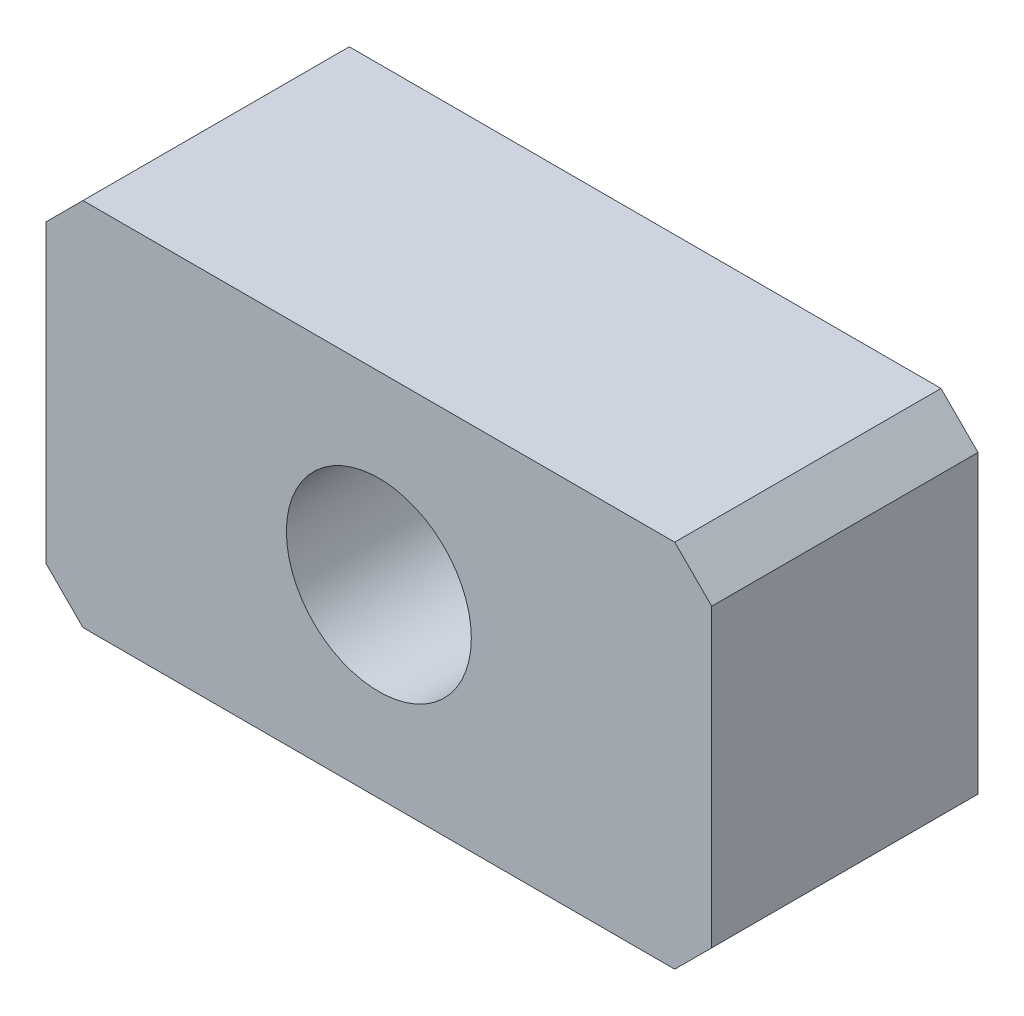
SolidWorks part; units mm, degrees
ref_plane "Front Plane" through (0, 0, 0) normal (0, 0, 1) x (1, 0, 0)
ref_plane "Top Plane" through (0, 0, 0) normal (0, 1, 0) x (1, 0, 0)
ref_plane "Right Plane" through (0, 0, 0) normal (1, 0, 0) x (0, 0, -1)
sketch "Sketch1" plane through (0, 0, 0) normal (0, 0, 1) x (1, 0, 0)
  line L1 (9, -5) -> (-9, -5)
  line L2 (9, -5) -> (9, 5)
  line L3 (9, 5) -> (-9, 5)
  line L4 (-9, -5) -> (-9, 5)
  line L5 (9, -5) -> (-9, 5) construction
  line L6 (9, 5) -> (-9, -5) construction
  circle A0 centre (0, 0) radius 2.5
  point P0 (0, 0)
  dimension "D3" = 5
  dimension "D1" = 18
  dimension "D2" = 10
extrude "Boss-Extrude1" add sketch "Sketch1" along normal blind 7.2
chamfer "Chamfer1" distance 1 angle 45 4 edges at (-9, -5, 3.6) (9, -5, 3.6) (9, 5, 3.6) (-9, 5, 3.6)
